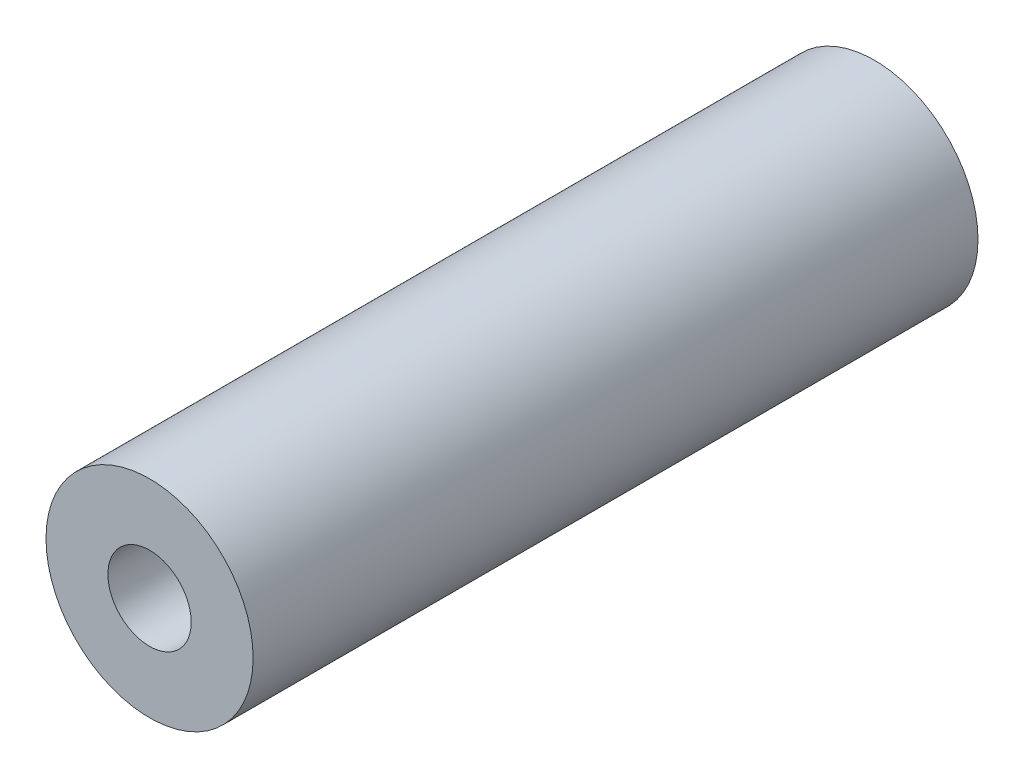
SolidWorks part; units mm, degrees
material "AISI 1020"
ref_plane "Front Plane" through (0, 0, 0) normal (0, 0, 1) x (1, 0, 0)
ref_plane "Top Plane" through (0, 0, 0) normal (0, 1, 0) x (1, 0, 0)
ref_plane "Right Plane" through (0, 0, 0) normal (1, 0, 0) x (0, 0, -1)
sketch "Sketch1" plane through (0, 0, 0) normal (0, 0, 1) x (1, 0, 0)
  circle A0 centre (0, 0) radius 6.35
  circle A1 centre (0, 0) radius 2.555
  dimension "D1" = 12.7
  dimension "D2" = 5.11
extrude "Boss-Extrude1" add sketch "Sketch1" along normal blind 44.45
cosmetic thread "Cosmetic Thread1" parameters "D2"=6.35
